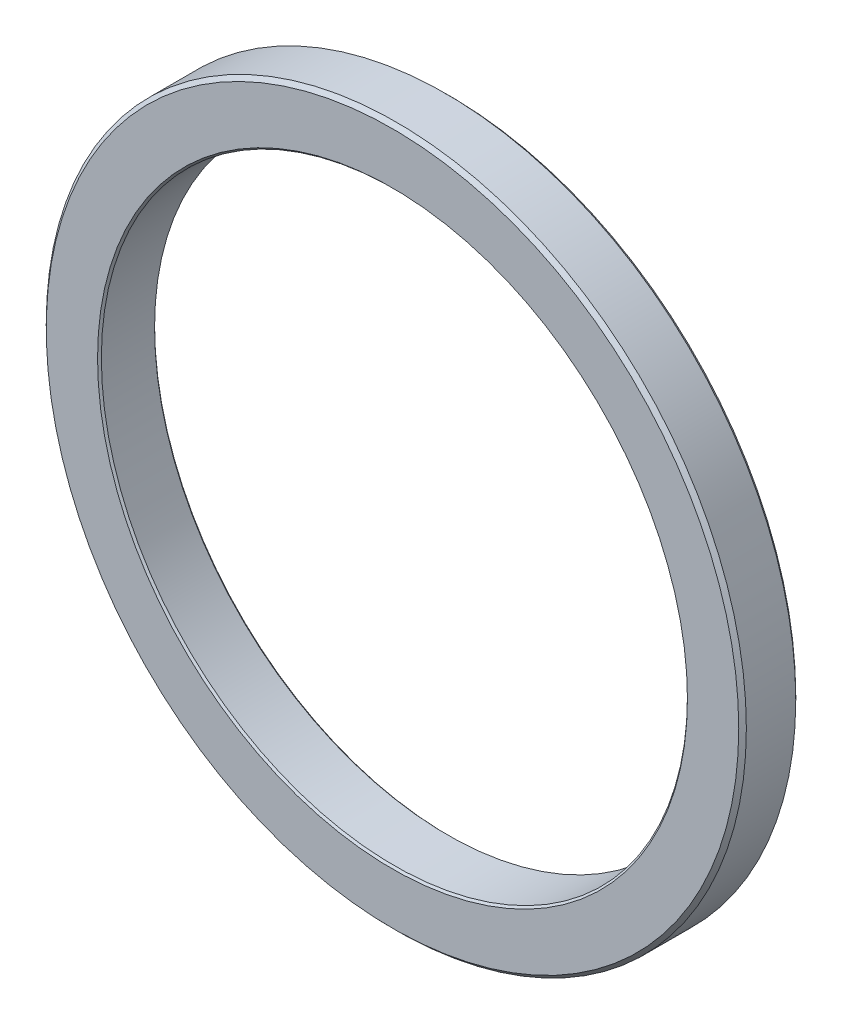
SolidWorks part; units mm, degrees
material "PETP Grey"
ref_plane "Front Plane" through (0, 0, 0) normal (0, 0, 1) x (1, 0, 0)
ref_plane "Top Plane" through (0, 0, 0) normal (0, 1, 0) x (1, 0, 0)
ref_plane "Right Plane" through (0, 0, 0) normal (1, 0, 0) x (0, 0, -1)
sketch "Sketch1" plane through (0, 0, 0) normal (1, 0, 0) x (0, 0, -1)
  line L0 (0, 0) -> (41.4438, 0) construction
  line L1 (0, 38.8) -> (0.25, 38.55)
  line L2 (0.5, 46.05) -> (7, 46.05)
  line L3 (0, 45.55) -> (0, 38.8)
  line L4 (0.25, 38.55) -> (7.25, 38.55)
  line L5 (7.5, 45.55) -> (7.5, 38.8)
  line L6 (7.25, 38.55) -> (7.5, 38.8)
  line L7 (0, 45.55) -> (0.5, 46.05)
  line L8 (7, 46.05) -> (7.5, 45.55)
  point P3 (0, 46.05)
  point P4 (7.5, 38.55)
  point P5 (0, 38.55)
  point P6 (7.5, 46.05)
  dimension "D1" = 77.1
  dimension "D2" = 92.1
  dimension "D3" = 7.5
revolve "Revolve1" add sketch "Sketch1" angle 360 about L0
